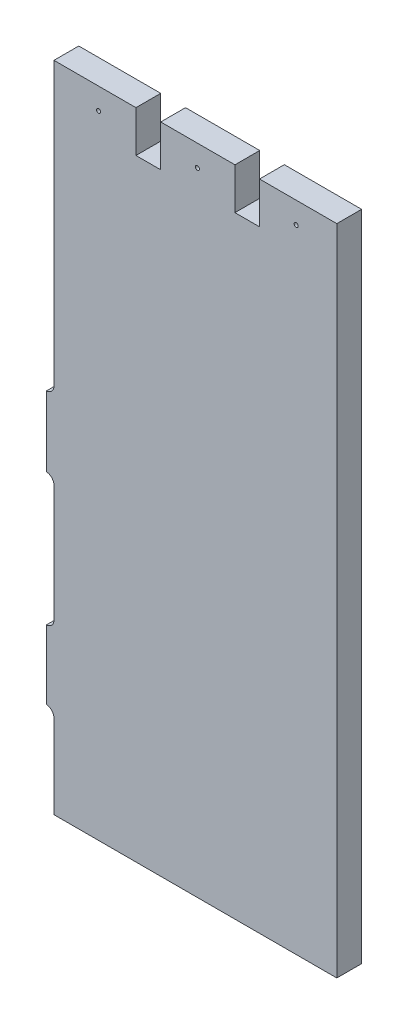
SolidWorks part; units mm, degrees
ref_plane "Plan de face" through (0, 0, 0) normal (0, 0, 1) x (1, 0, 0)
ref_plane "Plan de dessus" through (0, 0, 0) normal (0, 1, 0) x (1, 0, 0)
ref_plane "Plan de droite" through (0, 0, 0) normal (1, 0, 0) x (0, 0, -1)
ref_plane "Plan1" through (0, 0, 0) normal (0, 0, -1) x (-1, 0, 0)
sketch "Esquisse1" plane through (0, 0, 0) normal (0, 0, -1) x (-1, 0, 0)
  line L0 (-12.25, 17.8999) -> (-12.251, 10.578)
  line L1 (-13.25, 10.6) -> (-13.25, 17.9)
  line L2 (-12.239, 5.25) -> (-12.239, 0)
  line L3 (-12.239, 0) -> (0, 0)
  line L4 (0, 0) -> (0, 41)
  line L5 (0, 41) -> (-12.239, 41)
  line L6 (-12.239, 41) -> (-12.239, 23.3)
  line L7 (-13.25, 23.3) -> (-13.25, 41)
  line L8 (-13.25, 41) -> (-18.394, 41)
  line L9 (-18.394, 41) -> (-18.394, 38.4)
  line L10 (-18.394, 38.4) -> (-19.95, 38.4)
  line L11 (-19.95, 38.4) -> (-19.95, 41)
  line L12 (-19.95, 41) -> (-24.607, 41)
  line L13 (-24.607, 41) -> (-24.607, 38.4)
  line L14 (-24.607, 38.4) -> (-26.15, 38.4)
  line L15 (-26.15, 38.4) -> (-26.15, 41)
  line L16 (-26.15, 41) -> (-31, 41)
  line L17 (-31, 41) -> (-31, 0)
  line L18 (-31, 0) -> (-13.25, 0)
  line L19 (-13.25, 0) -> (-13.25, 5.25)
  circle A0 centre (-22.25, 39.65) radius 0.127
  circle A1 centre (-28.45, 39.65) radius 0.127
  circle A2 centre (-16.05, 39.65) radius 0.127
  circle A3 centre (-8.79, 35.815) radius 0.4
  arc A4 (-13.25, 17.9) -> (-12.25, 17.8999) centre (-12.75, 17.9) cw
  arc A5 (-12.251, 10.578) -> (-13.25, 10.6) centre (-12.7507, 10.5777) cw
  circle A6 centre (-6.25, 38.355) radius 0.4
  circle A7 centre (-3.71, 35.815) radius 0.4
  circle A8 centre (-3.59, 6.14) radius 0.4953
  circle A9 centre (-1.05, 6.14) radius 0.4953
  circle A10 centre (-1.05, 1.06) radius 0.4953
  circle A11 centre (-1.05, 3.6) radius 0.4953
  arc A12 (-12.239, 23.3) -> (-13.25, 23.3) centre (-12.7445, 23.3) cw
  arc A13 (-13.25, 5.25) -> (-12.239, 5.25) centre (-12.7445, 5.2505) cw
extrude "Boss.-Extru.1" add sketch "Esquisse1" against normal blind 1.5563
sketch "Esquisse2" plane through (0, 0, 1.5563) normal (0, 0, 1) x (1, 0, 0)
  line L1 (0, 41) -> (12.7747, 41)
  line L2 (0, 41) -> (0, 0)
  line L3 (0, 0) -> (12.7747, 0)
  line L4 (12.7747, 41) -> (12.7747, 0)
  line L5 (0, 41) -> (12.7747, 0) construction
  line L6 (0, 0) -> (12.7747, 41) construction
  point P4 (6.3874, 20.5)
extrude "Enlèv. mat.-Extru.1" cut sketch "Esquisse2" against normal through all
